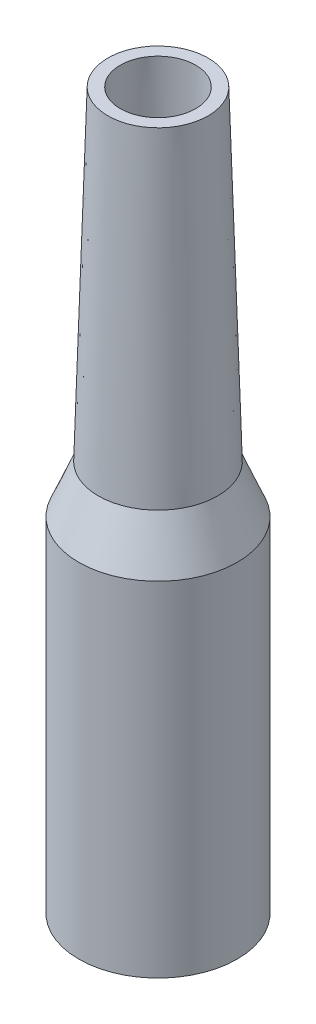
SolidWorks part; units mm, degrees
ref_plane "Front Plane" through (0, 0, 0) normal (0, 0, 1) x (1, 0, 0)
ref_plane "Top Plane" through (0, 0, 0) normal (0, 1, 0) x (1, 0, 0)
ref_plane "Right Plane" through (0, 0, 0) normal (1, 0, 0) x (0, 0, -1)
sketch "Sketch2" plane through (0, 0, 0) normal (0, 0, 1) x (1, 0, 0)
  line L1 (6.25, 0) -> (5.25, 33.9853)
  line L2 (5.25, 33.9853) -> (3.95, 33.9853)
  line L5 (0, -1000) -> (0, 49000) construction
  line L6 (3.95, 33.9853) -> (4.95, 0)
  line L7 (7, -5) -> (7, -41)
  line L8 (8.3, -5) -> (8.3, -41)
  line L10 (8.3, -41) -> (7, -41)
  line L12 (4.95, 0) -> (7, -5)
  line L13 (8.3, -5) -> (6.25, 0)
  dimension "D1" = 34
  dimension "D2" = 5.25
  dimension "D3" = 6.25
  dimension "D4" = 1.3
  dimension "D5" = 7
  dimension "D6" = 1.3
  dimension "D7" = 36
  dimension "D8" = 5
revolve "Revolve1" add sketch "Sketch2" angle 360 about L5
